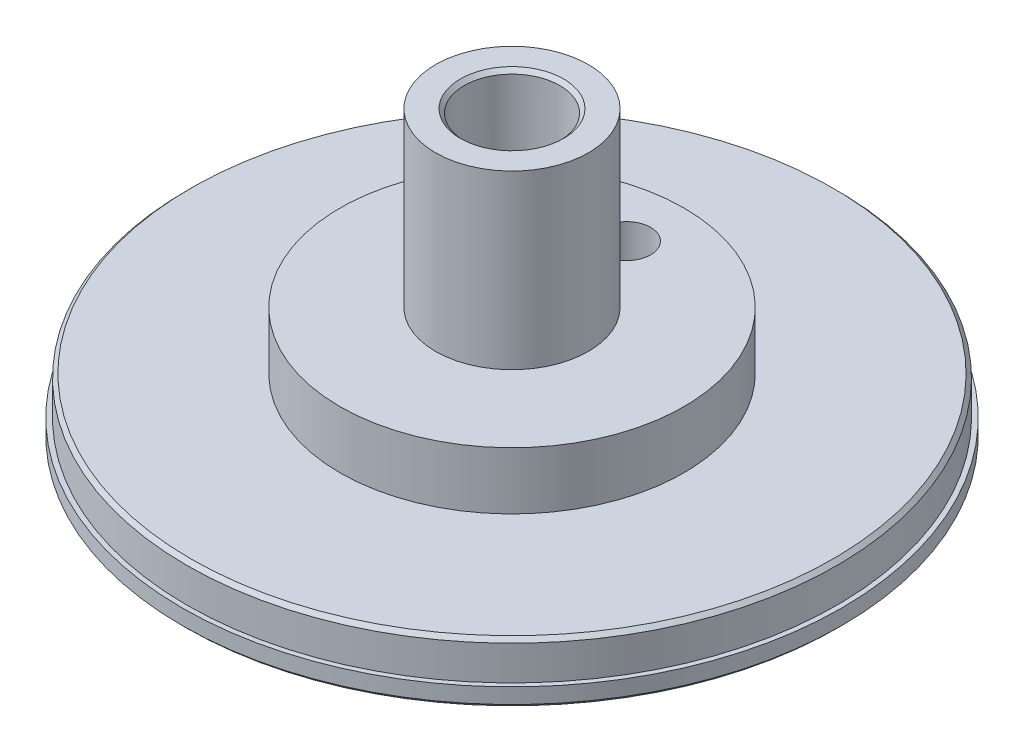
SolidWorks part; units mm, degrees
ref_plane "Front Plane" through (0, 0, 0) normal (0, 0, 1) x (1, 0, 0)
ref_plane "Top Plane" through (0, 0, 0) normal (0, 1, 0) x (1, 0, 0)
ref_plane "Right Plane" through (0, 0, 0) normal (1, 0, 0) x (0, 0, -1)
sketch "Sketch1" plane through (0, 0, 0) normal (0, 1, 0) x (1, 0, 0)
  circle A0 centre (0, 0) radius 17.25
  dimension "D1" = 34.5
extrude "Boss-Extrude1" add sketch "Sketch1" along normal blind 15
sketch "Sketch2" plane through (0, 15, 0) normal (0, 1, 0) x (1, 0, 0)
  circle A0 centre (0, 0) radius 17
  dimension "D1" = 34
extrude "Cut-Extrude1" cut sketch "Sketch2" against normal blind 14 flip side to cut
sketch "Sketch3" plane through (0, 15, 0) normal (0, 1, 0) x (1, 0, 0)
  circle A0 centre (0, 0) radius 9
  dimension "D1" = 18
extrude "Cut-Extrude4" cut sketch "Sketch3" against normal blind 12 flip side to cut
sketch "Sketch6" plane through (0, 15, 0) normal (0, 1, 0) x (1, 0, 0)
  circle A0 centre (0, 0) radius 4
  dimension "D1" = 8
extrude "Cut-Extrude5" cut sketch "Sketch6" against normal blind 9 flip side to cut
sketch "Sketch7" plane through (0, 15, 0) normal (0, 1, 0) x (1, 0, 0)
  circle A0 centre (0, 0) radius 2.5
  dimension "D1" = 5
extrude "Cut-Extrude6" cut sketch "Sketch7" against normal through all
sketch "Sketch8" plane through (0, 6, 0) normal (0, 1, 0) x (1, 0, 0)
  circle A0 centre (0, 6) radius 1.25
  dimension "D1" = 2.5
  dimension "D2" = 6
extrude "Cut-Extrude7" cut sketch "Sketch8" against normal through all
chamfer "Chamfer1" distance 0.2 angle 45 4 edges at (0, 0, 2.5) (0, 15, 2.5) (0, 3, 17) (0, 0, 17.25)
